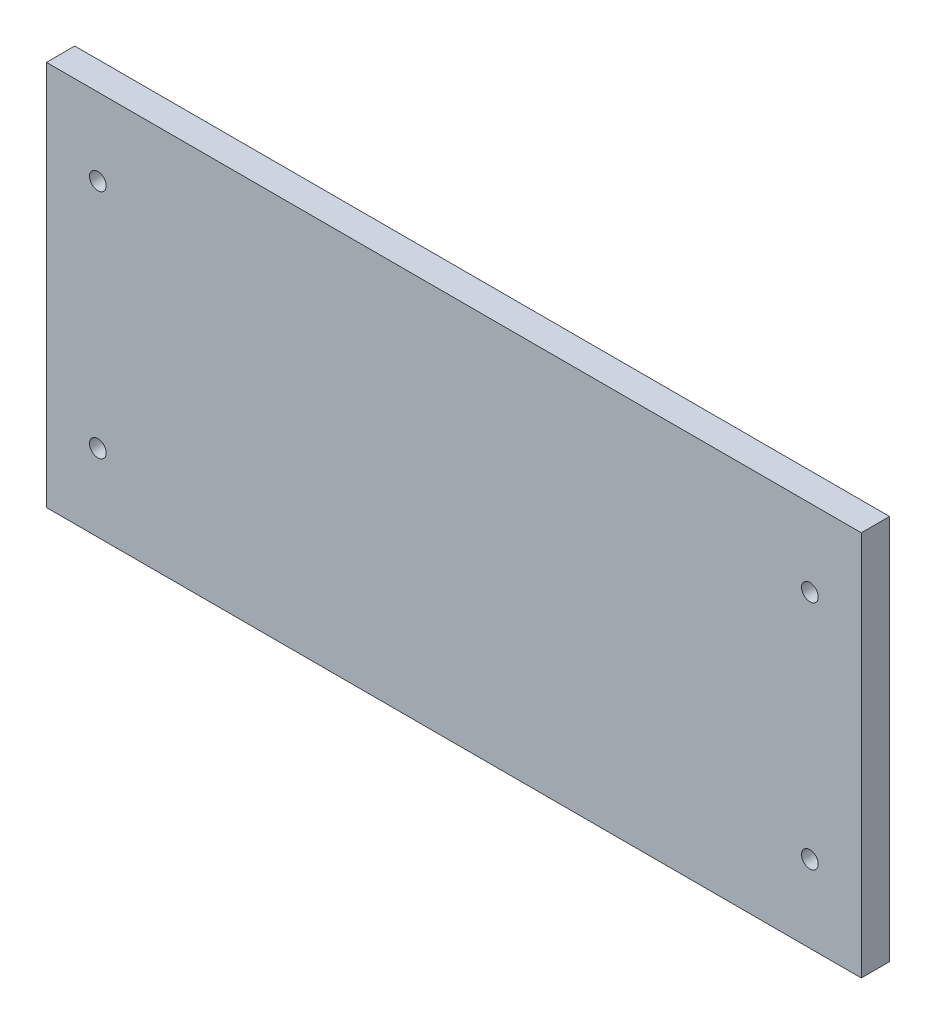
SolidWorks part; units mm, degrees
ref_plane "Alzado" through (0, 0, 0) normal (0, 0, 1) x (1, 0, 0)
ref_plane "Planta" through (0, 0, 0) normal (0, 1, 0) x (1, 0, 0)
ref_plane "Vista lateral" through (0, 0, 0) normal (1, 0, 0) x (0, 0, -1)
sketch "Sketch2" plane through (0, 0, 0) normal (0, 0, 1) x (1, 0, 0)
  line L0 (0, -55) -> (0, 55) construction
  line L1 (-158.5, -75) -> (158.5, -75)
  line L2 (-158.5, -75) -> (-158.5, 75)
  line L3 (-158.5, 75) -> (158.5, 75)
  line L4 (158.5, -75) -> (158.5, 75)
  line L5 (-158.5, -75) -> (158.5, 75) construction
  line L6 (-158.5, 75) -> (158.5, -75) construction
  line L7 (55, 0) -> (-55, 0) construction
  circle A0 centre (-138.5, 45) radius 3.25
  circle A1 centre (138.5, 45) radius 3.25
  circle A2 centre (138.5, -45) radius 3.25
  circle A3 centre (-138.5, -45) radius 3.25
  point P0 (0, 0)
  dimension "D3" = 6.5
  dimension "D1" = 317
  dimension "D2" = 150
  dimension "D4" = 30
  dimension "D5" = 20
extrude "Boss-Extrude1" add sketch "Sketch2" along normal blind 11
